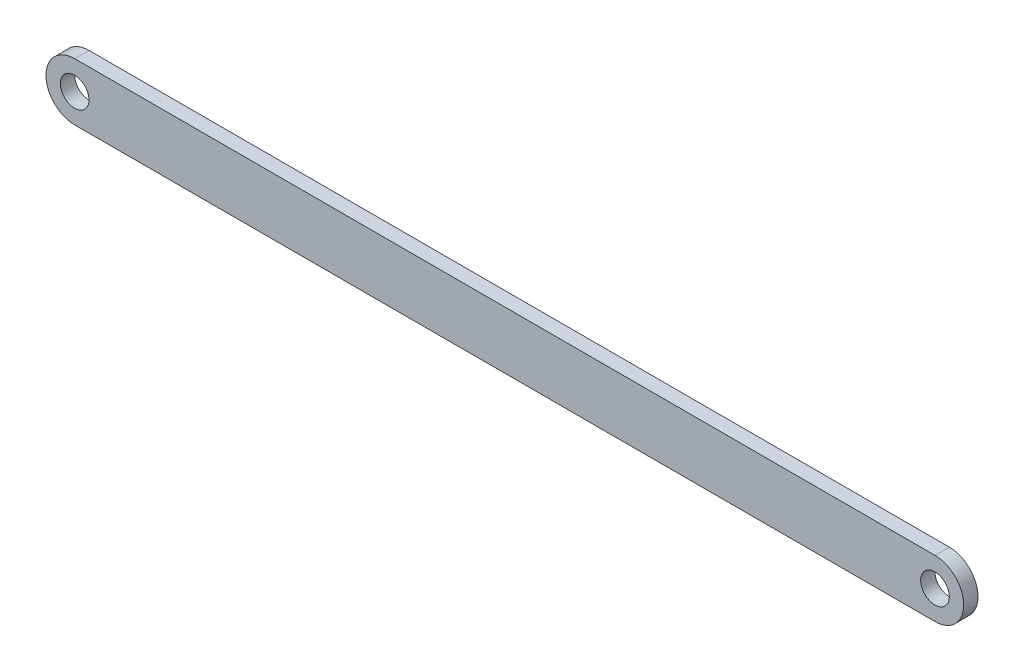
SolidWorks part; units mm, degrees
material "Plain Carbon Steel"
ref_plane "Front Plane" through (0, 0, 0) normal (0, 0, 1) x (1, 0, 0)
ref_plane "Top Plane" through (0, 0, 0) normal (0, 1, 0) x (1, 0, 0)
ref_plane "Right Plane" through (0, 0, 0) normal (1, 0, 0) x (0, 0, -1)
sketch "Sketch1" plane through (0, 0, 0) normal (0, 0, 1) x (1, 0, 0)
  line L0 (-952.5, 0) -> (952.5, 0) construction
  line L1 (-952.5, 63.5) -> (952.5, 63.5)
  line L2 (-952.5, -63.5) -> (952.5, -63.5)
  arc A0 (-952.5, 63.5) -> (-952.5, -63.5) centre (-952.5, 0) ccw
  arc A1 (952.5, -63.5) -> (952.5, 63.5) centre (952.5, 0) ccw
  point P2 (0, 0)
  dimension "D2" = 63.5
  dimension "D1" = 1905
extrude "Boss-Extrude1" add sketch "Sketch1" along normal blind 31.75
sketch "Sketch2" plane through (0, 0, 31.75) normal (0, 0, 1) x (1, 0, 0)
  circle A0 centre (-952.5, 0) radius 31.75
  circle A1 centre (952.5, 0) radius 31.75
  dimension "D1" = 63.5
extrude "Cut-Extrude1" cut sketch "Sketch2" against normal through all
